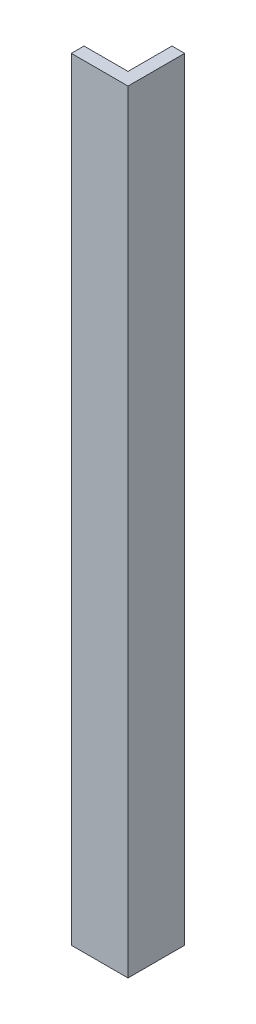
SolidWorks part; units mm, degrees
ref_plane "Front Plane" through (0, 0, 0) normal (0, 0, 1) x (1, 0, 0)
ref_plane "Top Plane" through (0, 0, 0) normal (0, 1, 0) x (1, 0, 0)
ref_plane "Right Plane" through (0, 0, 0) normal (1, 0, 0) x (0, 0, -1)
sketch "Sketch1" plane through (0, 0, 0) normal (0, 1, 0) x (1, 0, 0)
  line L1 (-3.175, 3.175) -> (-14.175, 3.175)
  line L2 (0, 14.175) -> (0, 0)
  line L3 (0, 0) -> (-14.175, 0)
  line L4 (-14.175, 3.175) -> (-14.175, 0)
  line L7 (0, 14.175) -> (-3.175, 14.175)
  line L8 (-3.175, 3.175) -> (-3.175, 14.175)
  dimension "D1" = 3.175
  dimension "D2" = 11
extrude "Boss-Extrude1" add sketch "Sketch1" along normal up to surface (193.175 mm away) contours L1 L4 L3 L2 L7 L8
